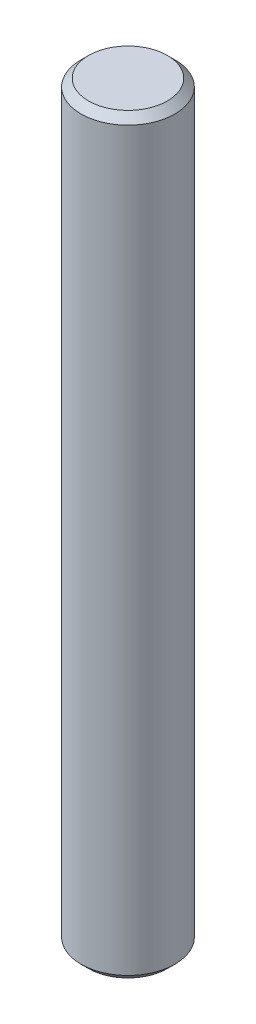
SolidWorks part; units mm, degrees
ref_plane "Ön Düzlem" through (0, 0, 0) normal (0, 0, 1) x (1, 0, 0)
ref_plane "Üst Düzlem" through (0, 0, 0) normal (0, 1, 0) x (1, 0, 0)
ref_plane "Sağ Düzlem" through (0, 0, 0) normal (1, 0, 0) x (0, 0, -1)
sketch "Çizim1" plane through (0, 0, 0) normal (0, 1, 0) x (1, 0, 0)
  circle A0 centre (0, 0) radius 12.5
  dimension "D1" = 25
extrude "Yükseklik-Ekstrüzyon1" add sketch "Çizim1" along normal blind 200
chamfer "Pah1" distance 2 angle 45 2 edges at (0, 0, 12.5) (0, 200, 12.5)
